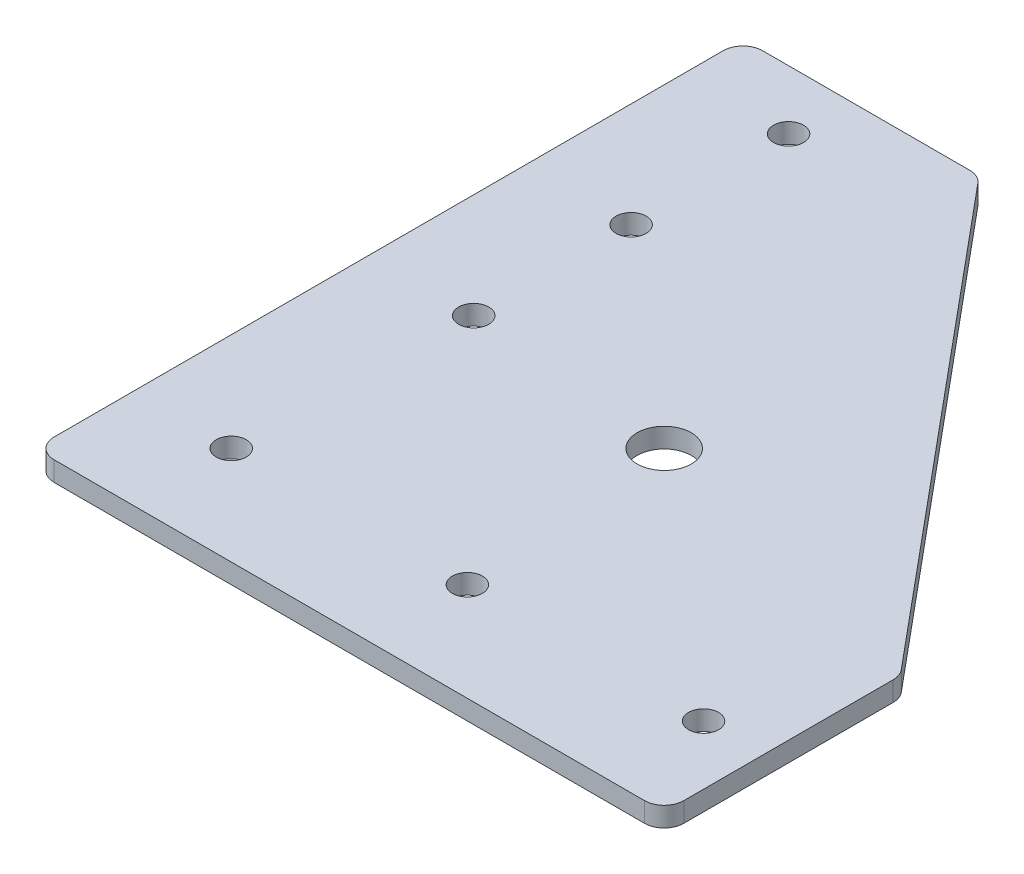
SolidWorks part; units mm, degrees
material "5052-H32"
ref_plane "Front" through (0, 0, 0) normal (0, 0, 1) x (1, 0, 0)
ref_plane "Top" through (0, 0, 0) normal (0, 1, 0) x (1, 0, 0)
ref_plane "Right" through (0, 0, 0) normal (1, 0, 0) x (0, 0, -1)
sketch "Sketch1" plane through (0, 0, 0) normal (0, 1, 0) x (1, 0, 0)
  line L0 (0, 0) -> (0, 114.3)
  line L1 (0, 114.3) -> (38.1, 114.3)
  line L2 (38.1, 114.3) -> (101.6, 38.1)
  line L3 (101.6, 38.1) -> (101.6, 0)
  line L4 (101.6, 0) -> (0, 0)
  circle A0 centre (15.875, 15.875) radius 2.4257
  circle A1 centre (53.975, 15.875) radius 2.4257
  circle A2 centre (92.075, 15.875) radius 2.4257
  circle A3 centre (16.891, 53.975) radius 2.4257
  circle A4 centre (16.891, 79.375) radius 2.4257
  circle A5 centre (16.891, 104.775) radius 2.4257
  dimension "D1" = 4.8514
  dimension "D2" = 15.875
  dimension "D3" = 15.875
  dimension "D5" = 38.1
  dimension "D6" = 53.975
  dimension "D7" = 16.891
  dimension "D9" = 38.1
  dimension "D10" = 38.1
  dimension "D11" = 101.6
  dimension "D12" = 114.3
  dimension "D13" = 25.4
  dimension "D4" = 3
  dimension "D8" = 3
extrude "Boss-Extrude1" add sketch "Sketch1" along normal blind 3.175
fillet "Fillet1" radius 3.175 5 edges at (0, 1.5875, 0) (0, 1.5875, -114.3) (38.1, 1.5875, -114.3) (101.6, 1.5875, -38.1) (101.6, 1.5875, 0)
sketch "Sketch2" plane through (0, 0, 0) normal (0, -1, 0) x (1, 0, 0)
  line L0 (0, -111.125) -> (0, -3.175) construction
  line L1 (3.175, 0) -> (98.425, 0) construction
  circle A0 centre (50.8, -50.8) radius 4.3688
  dimension "D1" = 8.7376
  dimension "D2" = 50.8
  dimension "D3" = 50.8
extrude "Cut-Extrude1" cut sketch "Sketch2" against normal through all
